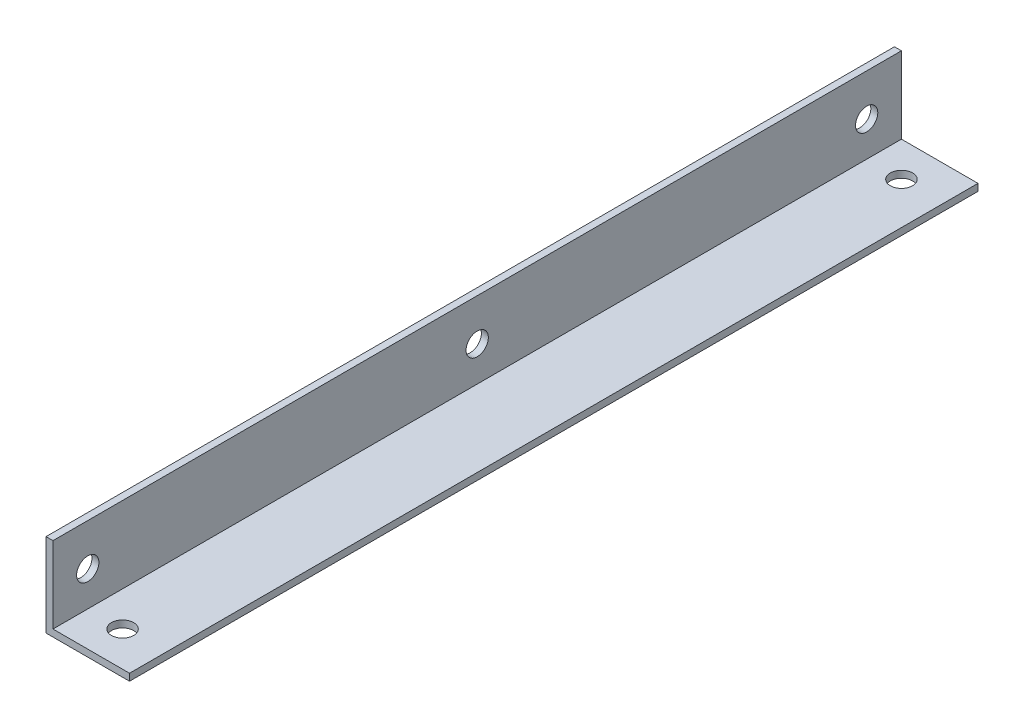
SolidWorks part; units mm, degrees
ref_plane "Front Plane" through (0, 0, 0) normal (0, 0, 1) x (1, 0, 0)
ref_plane "Top Plane" through (0, 0, 0) normal (0, 1, 0) x (1, 0, 0)
ref_plane "Right Plane" through (0, 0, 0) normal (1, 0, 0) x (0, 0, -1)
sketch "Sketch1" plane through (0, 0, 0) normal (0, 0, 1) x (1, 0, 0)
  line L0 (0, 0) -> (0, 30)
  line L1 (0, 30) -> (2.5, 30)
  line L2 (2.5, 30) -> (2.5, 2.5)
  line L3 (2.5, 2.5) -> (30, 2.5)
  line L4 (30, 2.5) -> (30, 0)
  line L5 (30, 0) -> (0, 0)
  dimension "D1" = 2.5
  dimension "D2" = 2.5
  dimension "D3" = 30
  dimension "D4" = 30
extrude "Boss-Extrude1" add sketch "Sketch1" along normal blind 304.8
sketch "Sketch2" plane through (0, 2.5, 0) normal (0, 1, 0) x (1, 0, 0)
  line L0 (30, -304.8) -> (2.5, -304.8) construction
  line L1 (30, 0) -> (2.5, 0) construction
  line L2 (30, -304.8) -> (30, 0) construction
  circle A0 centre (15, -12.5) radius 4
  circle A1 centre (15, -292.3) radius 4
  point P0 (16.25, -304.8)
  dimension "D2" = 8
  dimension "D1" = 12.5
  dimension "D3" = 15
  dimension "D4" = 12.5
extrude "Cut-Extrude1" cut sketch "Sketch2" against normal through all
sketch "Sketch3" plane through (2.5, 0, 0) normal (1, 0, 0) x (0, 0, -1)
  line L0 (-152.4, 62.6514) -> (-152.4, -41.7268) construction
  line L1 (0, 2.5) -> (0, 30) construction
  line L2 (-304.8, 30) -> (0, 30) construction
  circle A0 centre (-12.5, 15) radius 4
  circle A1 centre (-292.3, 15) radius 4
  dimension "D2" = 8
  dimension "D1" = 152.4
  dimension "D3" = 12.5
  dimension "D4" = 15
extrude "Cut-Extrude2" cut sketch "Sketch3" against normal through all
sketch "Sketch5" plane through (2.5, 0, 0) normal (1, 0, 0) x (0, 0, -1)
  line L0 (0, 2.5) -> (0, 30) construction
  line L1 (-304.8, 30) -> (0, 30) construction
  circle A0 centre (-152.4, 15) radius 4
  dimension "D1" = 8
  dimension "D2" = 152.4
  dimension "D3" = 15
extrude "Cut-Extrude3" cut sketch "Sketch5" against normal through all
